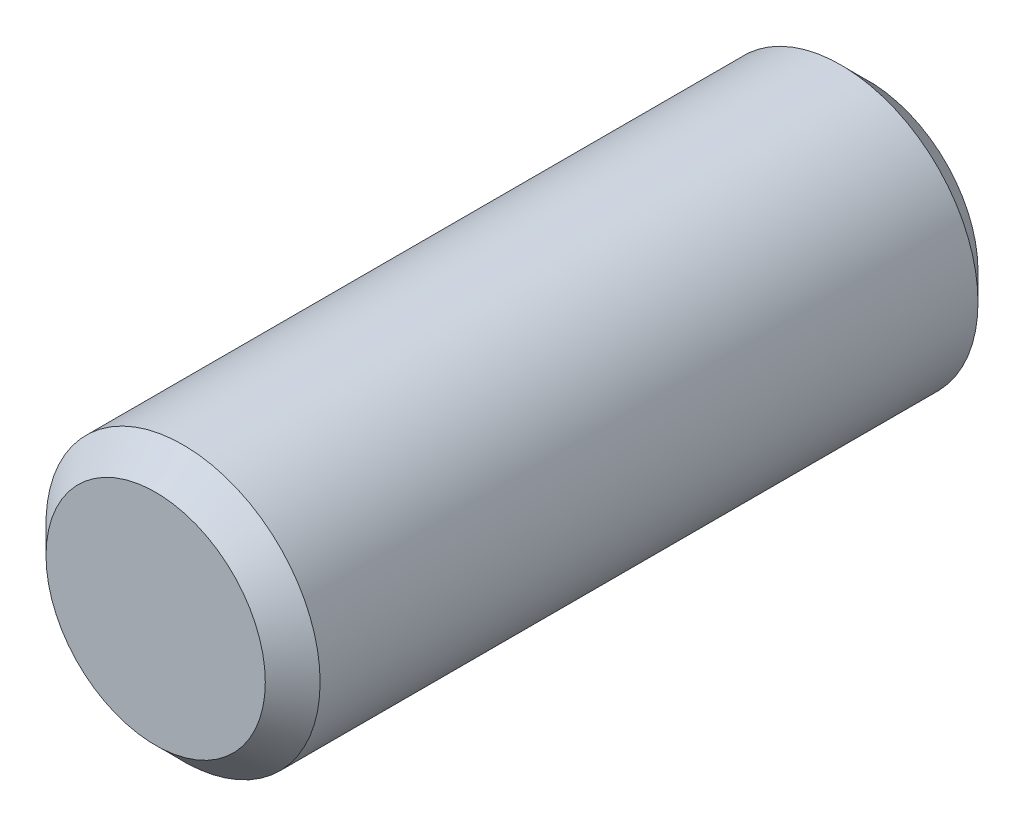
SolidWorks part; units mm, degrees
ref_plane "Front Plane" through (0, 0, 0) normal (0, 0, 1) x (1, 0, 0)
ref_plane "Top Plane" through (0, 0, 0) normal (0, 1, 0) x (1, 0, 0)
ref_plane "Right Plane" through (0, 0, 0) normal (1, 0, 0) x (0, 0, -1)
sketch "Sketch1" plane through (0, 0, 0) normal (0, 0, 1) x (1, 0, 0)
  circle A0 centre (0, 0) radius 10
  dimension "D1" = 20
extrude "Boss-Extrude1" add sketch "Sketch1" against normal blind 52
chamfer "Chamfer2" distance 2 angle 45 2 edges at (10, 0, -52) (10, 0, 0)
